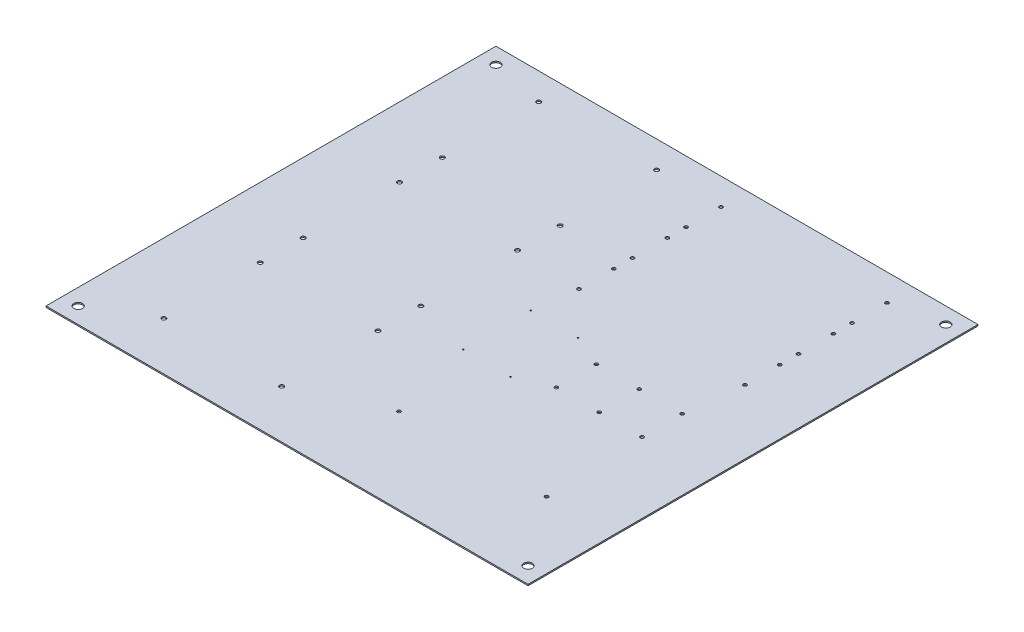
SolidWorks part; units mm, degrees
ref_plane "Front Plane" through (0, 0, 0) normal (0, 0, 1) x (1, 0, 0)
ref_plane "Top Plane" through (0, 0, 0) normal (0, 1, 0) x (1, 0, 0)
ref_plane "Right Plane" through (0, 0, 0) normal (1, 0, 0) x (0, 0, -1)
sketch "Sketch1" plane through (0, 0, 0) normal (0, 1, 0) x (1, 0, 0)
  line L1 (0, 0) -> (571.5, 0)
  line L2 (0, 0) -> (0, 533.4)
  line L3 (0, 533.4) -> (571.5, 533.4)
  line L4 (571.5, 0) -> (571.5, 533.4)
  dimension "D1" = 533.4
  dimension "D2" = 571.5
extrude "Boss-Extrude1" add sketch "Sketch1" along normal blind 1.5875
hole_wizard "#10-32 Tapped Hole1" positions "Sketch3" profile "Sketch2" tap size "#10-32" standard "ANSI Inch" end condition through all
sketch "Sketch3" plane through (0, 1.5875, 0) normal (0, 1, 0) x (1, 0, 0)
  line L0 (571.5, 533.4) -> (0, 533.4) construction
  line L1 (0, 533.4) -> (0, 0) construction
  point P0 (298.45, 501.65)
  point P2 (495.3, 501.65)
  point P4 (298.45, 460.375)
  point P6 (495.3, 460.375)
  point P21 (298.45, 438.15)
  point P22 (495.3, 438.15)
  point P23 (298.45, 396.875)
  point P24 (495.3, 396.875)
  point P25 (298.45, 374.65)
  point P26 (495.3, 374.65)
  point P27 (298.45, 333.375)
  point P28 (495.3, 333.375)
  dimension "D1" = 196.85
  dimension "D2" = 41.275
  dimension "D3" = 31.75
  dimension "D4" = 298.45
  dimension "D6" = 63.5
  dimension "D5" = 3
sketch "Sketch2" plane through (298.45, 1.5875, -501.65) normal (1, 0, 0) x (0, 0, 1)
  line L0 (0, 0) -> (0, 1.5875)
  line L1 (0, 1.5875) -> (2.0193, 1.5875)
  line L2 (2.0193, 1.5875) -> (2.0193, 0)
  line L5 (2.0193, 0) -> (0, 0)
  line L11 (0, -6.35) -> (0, 107.95) construction
  dimension "Thru Tap Drill Dia." = 4.0386
  dimension "Thru Tap Drill Depth" = 1.5875
cosmetic thread "Hole Thread1"
cosmetic thread "Hole Thread2"
cosmetic thread "Hole Thread3"
cosmetic thread "Hole Thread4"
cosmetic thread "Hole Thread17"
cosmetic thread "Hole Thread18"
cosmetic thread "Hole Thread19"
cosmetic thread "Hole Thread20"
cosmetic thread "Hole Thread21"
cosmetic thread "Hole Thread22"
cosmetic thread "Hole Thread23"
cosmetic thread "Hole Thread24"
hole_wizard "1/4-20 Tapped Hole1" positions "Sketch4" profile "Sketch5" tap size "1/4-20" standard "ANSI Inch" end condition through all
sketch "Sketch4" plane through (0, 1.5875, 0) normal (0, 1, 0) x (1, 0, 0)
  line L0 (571.5, 533.4) -> (0, 533.4) construction
  line L1 (0, 533.4) -> (0, 0) construction
  point P0 (82.55, 501.65)
  point P2 (82.55, 387.35)
  point P4 (222.25, 387.35)
  point P6 (222.25, 501.65)
  point P23 (82.55, 336.55)
  point P24 (82.55, 222.25)
  point P25 (222.25, 222.25)
  point P26 (222.25, 336.55)
  point P27 (82.55, 171.45)
  point P28 (82.55, 57.15)
  point P29 (222.25, 57.15)
  point P30 (222.25, 171.45)
  dimension "D1" = 114.3
  dimension "D2" = 139.7
  dimension "D3" = 31.75
  dimension "D4" = 82.55
  dimension "D6" = 50.8
  dimension "D5" = 3
sketch "Sketch5" plane through (82.55, 1.5875, -501.65) normal (1, 0, 0) x (0, 0, 1)
  line L0 (0, 0) -> (0, 1.5875)
  line L1 (0, 1.5875) -> (2.5527, 1.5875)
  line L2 (2.5527, 1.5875) -> (2.5527, 0)
  line L5 (2.5527, 0) -> (0, 0)
  line L11 (0, -6.35) -> (0, 107.95) construction
  dimension "Thru Tap Drill Dia." = 5.1054
  dimension "Thru Tap Drill Depth" = 1.5875
cosmetic thread "Hole Thread5"
cosmetic thread "Hole Thread6"
cosmetic thread "Hole Thread7"
cosmetic thread "Hole Thread8"
cosmetic thread "Hole Thread9"
cosmetic thread "Hole Thread10"
cosmetic thread "Hole Thread11"
cosmetic thread "Hole Thread12"
cosmetic thread "Hole Thread13"
cosmetic thread "Hole Thread14"
cosmetic thread "Hole Thread15"
cosmetic thread "Hole Thread16"
hole_wizard "M2x0.4 Tapped Hole1" positions "Sketch6" profile "Sketch7" tap size "M2x0.4" standard "ANSI Metric" end condition through all
sketch "Sketch6" plane through (0, 1.5875, 0) normal (0, 1, 0) x (1, 0, 0)
  line L0 (0, 533.4) -> (0, 0) construction
  circle A1 centre (298.45, 333.375) radius 2.0193 construction
  point P0 (292.1, 282.575)
  point P2 (348.1, 282.575)
  point P4 (292.1, 202.575)
  point P6 (348.1, 202.575)
  dimension "D1" = 80
  dimension "D2" = 56
  dimension "D3" = 292.1
  dimension "D4" = 50.8
sketch "Sketch7" plane through (292.1, 1.5875, -282.575) normal (1, 0, 0) x (0, 0, 1)
  line L0 (0, 0) -> (0, 1.5875)
  line L1 (0, 1.5875) -> (0.8, 1.5875)
  line L2 (0.8, 1.5875) -> (0.8, 0)
  line L5 (0.8, 0) -> (0, 0)
  line L11 (0, -6.35) -> (0, 107.95) construction
  dimension "Thru Tap Drill Dia." = 1.6
  dimension "Thru Tap Drill Depth" = 1.5875
cosmetic thread "Hole Thread25"
cosmetic thread "Hole Thread26"
cosmetic thread "Hole Thread27"
cosmetic thread "Hole Thread28"
hole_wizard "#10-32 Tapped Hole2" positions "Sketch8" profile "Sketch9" tap size "#10-32" standard "ANSI Inch" end condition through all
sketch "Sketch8" plane through (0, 1.5875, 0) normal (0, 1, 0) x (1, 0, 0)
  circle A4 centre (348.1, 282.575) radius 0.8 construction
  point P0 (386.2, 266.324)
  point P2 (386.2, 218.826)
  point P22 (437, 266.324)
  point P23 (437, 218.826)
  point P24 (487.8, 266.324)
  point P25 (487.8, 218.826)
  dimension "D2" = 16.251
  dimension "D3" = 38.1
  dimension "D1" = 47.498
  dimension "D5" = 50.8
  dimension "D4" = 3
sketch "Sketch9" plane through (386.2, 1.5875, -266.324) normal (1, 0, 0) x (0, 0, 1)
  line L0 (0, 0) -> (0, 1.5875)
  line L1 (0, 1.5875) -> (2.0193, 1.5875)
  line L2 (2.0193, 1.5875) -> (2.0193, 0)
  line L5 (2.0193, 0) -> (0, 0)
  line L11 (0, -6.35) -> (0, 107.95) construction
  dimension "Thru Tap Drill Dia." = 4.0386
  dimension "Thru Tap Drill Depth" = 1.5875
cosmetic thread "Hole Thread29"
cosmetic thread "Hole Thread30"
cosmetic thread "Hole Thread31"
cosmetic thread "Hole Thread32"
cosmetic thread "Hole Thread33"
cosmetic thread "Hole Thread34"
hole_wizard "#10-32 Tapped Hole3" positions "Sketch10" profile "Sketch11" tap size "#10-32" standard "ANSI Inch" end condition through all
sketch "Sketch10" plane through (0, 1.5875, 0) normal (0, 1, 0) x (1, 0, 0)
  line L0 (0, 533.4) -> (0, 0) construction
  circle A0 centre (348.1, 202.575) radius 0.8 construction
  point P0 (317.5, 100.975)
  point P2 (492.506, 100.975)
  dimension "D1" = 175.006
  dimension "D2" = 101.6
  dimension "D3" = 317.5
sketch "Sketch11" plane through (317.5, 1.5875, -100.975) normal (1, 0, 0) x (0, 0, 1)
  line L0 (0, 0) -> (0, 1.5875)
  line L1 (0, 1.5875) -> (2.0193, 1.5875)
  line L2 (2.0193, 1.5875) -> (2.0193, 0)
  line L5 (2.0193, 0) -> (0, 0)
  line L11 (0, -6.35) -> (0, 107.95) construction
  dimension "Thru Tap Drill Dia." = 4.0386
  dimension "Thru Tap Drill Depth" = 1.5875
cosmetic thread "Hole Thread35"
cosmetic thread "Hole Thread36"
hole_wizard "3/8 Clearance Hole1" positions "Sketch12" profile "Sketch13" hole size "3/8" standard "ANSI Inch" end condition through all
sketch "Sketch12" plane through (0, 1.5875, 0) normal (0, 1, 0) x (1, 0, 0)
  line L0 (0, 266.7) -> (-33.6931, 266.7)
  line L1 (0, 533.4) -> (0, 0) construction
  line L3 (285.75, 533.4) -> (285.75, 552.2627)
  line L4 (571.5, 533.4) -> (0, 533.4) construction
  point P0 (19.05, 514.35)
  point P14 (552.45, 514.35)
  point P15 (552.45, 19.05)
  point P16 (19.05, 19.05)
  dimension "D1" = 495.3
  dimension "D2" = 533.4
sketch "Sketch13" plane through (19.05, 1.5875, -514.35) normal (1, 0, 0) x (0, 0, 1)
  line L0 (0, 0) -> (0, 1.5875)
  line L1 (0, 1.5875) -> (5.1587, 1.5875)
  line L2 (5.1587, 1.5875) -> (5.1587, 0)
  line L5 (5.1587, 0) -> (0, 0)
  line L11 (0, -6.35) -> (0, 107.95) construction
  dimension "Thru Hole Dia." = 10.3175
  dimension "Thru Hole Depth" = 1.5875
